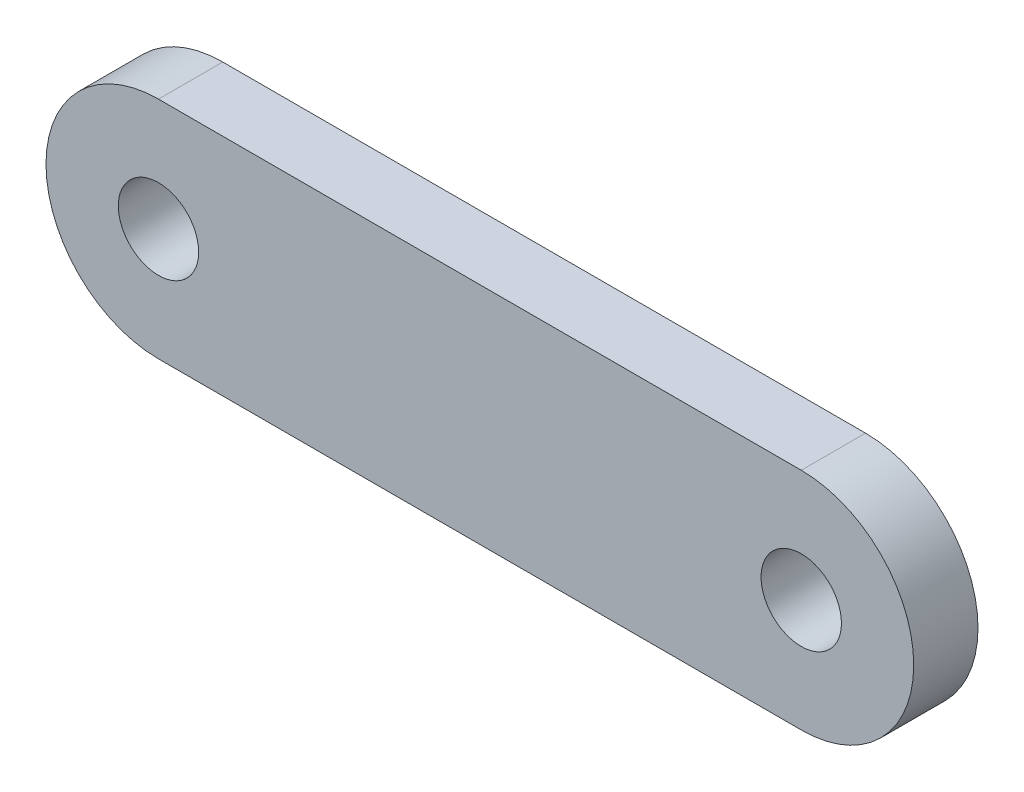
SolidWorks part; units mm, degrees
ref_plane "Plan de face" through (0, 0, 0) normal (0, 0, 1) x (1, 0, 0)
ref_plane "Plan de dessus" through (0, 0, 0) normal (0, 1, 0) x (1, 0, 0)
ref_plane "Plan de droite" through (0, 0, 0) normal (1, 0, 0) x (0, 0, -1)
sketch "Esquisse1" plane through (0, 0, 0) normal (0, 0, 1) x (1, 0, 0)
  line L0 (0, 0) -> (40, 0) construction
  line L1 (0, 7) -> (40, 7)
  line L2 (0, -7) -> (40, -7)
  arc A0 (0, 7) -> (0, -7) centre (0, 0) ccw
  arc A1 (40, -7) -> (40, 7) centre (40, 0) ccw
  circle A2 centre (0, 0) radius 2.5
  circle A3 centre (40, 0) radius 2.5
  point P3 (20, 0)
  dimension "D2" = 7
  dimension "D3" = 5
  dimension "D4" = 5
  dimension "D1" = 40
extrude "Boss.-Extru.1" add sketch "Esquisse1" along normal blind 4
